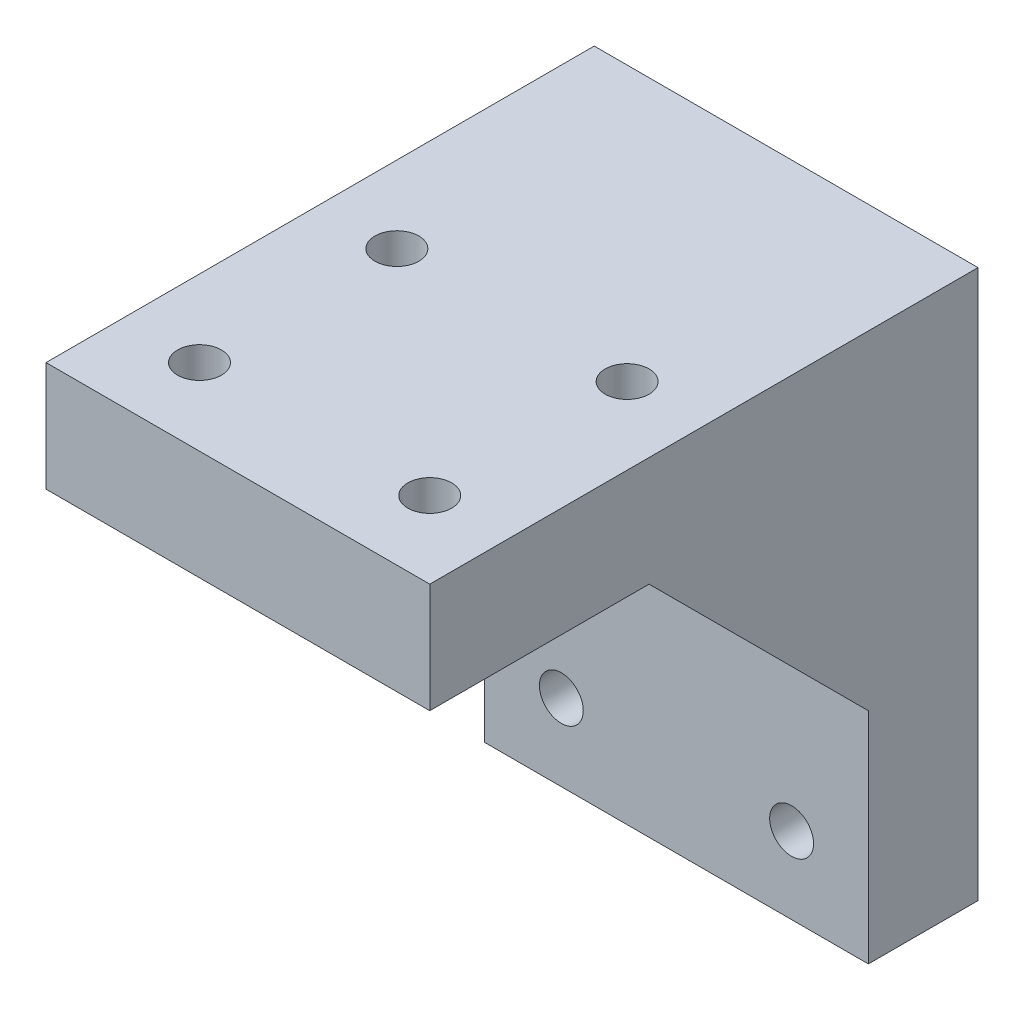
SolidWorks part; units mm, degrees
ref_plane "Front Plane" through (0, 0, 0) normal (0, 0, 1) x (1, 0, 0)
ref_plane "Top Plane" through (0, 0, 0) normal (0, 1, 0) x (1, 0, 0)
ref_plane "Right Plane" through (0, 0, 0) normal (1, 0, 0) x (0, 0, -1)
sketch "Sketch1" plane through (0, 0, 0) normal (0, 0, 1) x (1, 0, 0)
  line L1 (-22.8049, 43.5671) -> (12.1951, 43.5671)
  line L2 (-22.8049, 43.5671) -> (-22.8049, -6.4329)
  line L3 (-22.8049, -6.4329) -> (12.1951, -6.4329)
  line L4 (12.1951, 43.5671) -> (12.1951, -6.4329)
  dimension "D1" = 35
  dimension "D2" = 50
extrude "Boss-Extrude1" add sketch "Sketch1" along normal blind 10
sketch "Sketch2" plane through (0, 0, 10) normal (0, 0, 1) x (1, 0, 0)
  line L0 (12.1951, -6.4329) -> (12.1951, 43.5671) construction
  line L1 (-22.8049, 43.5671) -> (12.1951, 43.5671)
  line L2 (-22.8049, 43.5671) -> (-22.8049, 33.5671)
  line L3 (-22.8049, 33.5671) -> (12.1951, 33.5671)
  line L4 (12.1951, 43.5671) -> (12.1951, 33.5671)
  dimension "D1" = 10
extrude "Boss-Extrude2" add sketch "Sketch2" along normal blind 40
sketch "Sketch3" plane through (0, 0, 10) normal (0, 0, 1) x (1, 0, 0)
  line L0 (-22.8049, -6.4329) -> (12.1951, -6.4329) construction
  line L1 (-22.8049, 33.5671) -> (-22.8049, -6.4329) construction
  line L2 (12.1951, -6.4329) -> (12.1951, 33.5671) construction
  line L3 (-22.8049, 33.5671) -> (12.1951, 33.5671) construction
  circle A0 centre (5.1951, 0.5671) radius 2
  circle A1 centre (-15.8049, 18.5671) radius 2
  circle A2 centre (5.1951, 18.5671) radius 2
  circle A3 centre (-15.8049, 0.5671) radius 2
  dimension "D1" = 4
  dimension "D2" = 4
  dimension "D3" = 4
  dimension "D4" = 4
  dimension "D5" = 7
  dimension "D6" = 0
  dimension "D7" = 7
  dimension "D8" = 7
  dimension "D9" = 15
  dimension "D10" = 0
  dimension "D11" = 0
  dimension "D12" = 0
extrude "Cut-Extrude1" cut sketch "Sketch3" against normal blind 30
sketch "Sketch4" plane through (0, 33.5671, 0) normal (0, -1, 0) x (1, 0, 0)
  line L0 (-22.8049, 50) -> (-22.8049, 10) construction
  line L1 (12.1951, 50) -> (12.1951, 10) construction
  line L2 (-22.8049, 50) -> (12.1951, 50) construction
  line L3 (-22.8049, 10) -> (12.1951, 10) construction
  circle A0 centre (-15.8049, 43) radius 2
  circle A1 centre (5.1951, 43) radius 2
  circle A2 centre (-15.8049, 25) radius 2
  circle A3 centre (5.1951, 25) radius 2
  dimension "D1" = 4
  dimension "D2" = 4
  dimension "D3" = 4
  dimension "D4" = 4
  dimension "D5" = 7
  dimension "D6" = 7
  dimension "D7" = 0
  dimension "D8" = 7
  dimension "D9" = 7
  dimension "D10" = 7
  dimension "D11" = 15
  dimension "D12" = 0
extrude "Cut-Extrude2" cut sketch "Sketch4" against normal blind 30
sketch "Sketch5" plane through (-22.8049, 0, 0) normal (-1, 0, 0) x (0, 0, 1)
  line L0 (30, 33.5671) -> (10, 13.5671)
  line L1 (50, 33.5671) -> (10, 33.5671) construction
  line L2 (10, 33.5671) -> (10, -6.4329) construction
  line L3 (10, 13.5671) -> (10, 33.5671)
  line L4 (10, 33.5671) -> (30, 33.5671)
  dimension "D1" = 20
  dimension "D2" = 20
extrude "Boss-Extrude3" add sketch "Sketch5" against normal up to vertex (35 mm away)
sketch "Sketch6" plane through (0, 33.5671, 0) normal (0, 1, 0) x (1, 0, 0)
  circle A0 centre (5.1951, -25) radius 3.5
  circle A1 centre (-15.8049, -25) radius 3.5
  dimension "D1" = 7
  dimension "D2" = 7
extrude "Cut-Extrude3" cut sketch "Sketch6" against normal blind 30
sketch "Sketch7" plane through (0, 0, 10) normal (0, 0, -1) x (-1, 0, 0)
  circle A0 centre (-5.1951, 18.5671) radius 3.5
  circle A1 centre (15.8049, 18.5671) radius 3.5
  dimension "D1" = 7
  dimension "D2" = 7
extrude "Cut-Extrude4" cut sketch "Sketch7" against normal blind 30
